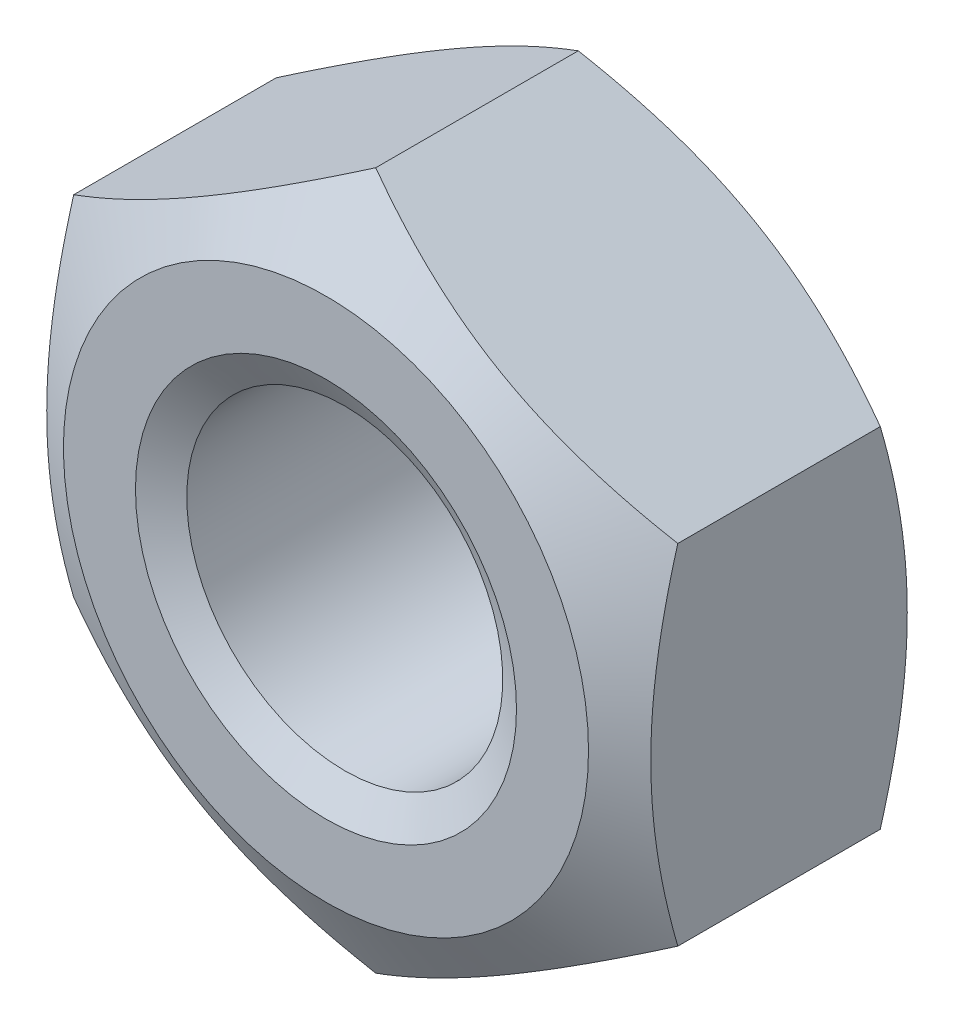
SolidWorks part; units mm, degrees
ref_plane "Front Plane" through (0, 0, 0) normal (0, 0, 1) x (1, 0, 0)
ref_plane "Top Plane" through (0, 0, 0) normal (0, 1, 0) x (1, 0, 0)
ref_plane "Right Plane" through (0, 0, 0) normal (1, 0, 0) x (0, 0, -1)
sketch "Sketch1" plane through (0, 0, 0) normal (0, 0, 1) x (1, 0, 0)
  line L0 (0, 0) -> (0, 7.5056) construction
  line L1 (0, 7.5056) -> (-6.5, 3.7528)
  line L2 (-6.5, 3.7528) -> (-6.5, -3.7528)
  line L3 (-6.5, -3.7528) -> (0, -7.5056)
  line L4 (0, -7.5056) -> (6.5, -3.7528)
  line L5 (6.5, -3.7528) -> (6.5, 3.7528)
  line L6 (6.5, 3.7528) -> (0, 7.5056)
  circle A0 centre (0, 0) radius 6.5 construction
  dimension "S DIM" = 13
extrude "Boss-Extrude1" add sketch "Sketch1" against normal blind 6.5
sketch "Sketch4" plane through (0, 0, 0) normal (1, 0, 0) x (0, 0, -1)
  line L0 (6.5, 7.5056) -> (5.4287, 7.5056)
  line L1 (6.5, 7.5056) -> (0, 7.5056) construction
  line L2 (5.4287, 7.5056) -> (6.5, 5.65)
  line L4 (6.5, 5.65) -> (6.5, 7.5056)
  line L5 (0, 0) -> (3.2979, 0) construction
  line L6 (0, 7.5056) -> (1.0713, 7.5056)
  line L7 (1.0713, 7.5056) -> (0, 5.65)
  line L9 (0, 5.65) -> (0, 7.5056)
  dimension "SAME S 1" = 11.3
  dimension "D2" = 30
  dimension "SAME S 2" = 11.3
  dimension "D4" = 30
revolve "Cut-Revolve1" cut sketch "Sketch4" angle 360 about L5
sketch "Sketch5" plane through (0, 0, 0) normal (1, 0, 0) x (0, 0, -1)
  line L0 (0, 0) -> (6.5, 0) construction
  line L1 (0, 0) -> (0, 4.1)
  line L2 (0, 5.65) -> (0, -5.65) construction
  line L3 (0, 4.1) -> (0.4041, 3.4)
  line L4 (0.4041, 3.4) -> (6.0959, 3.4)
  line L5 (6.0959, 3.4) -> (6.5, 4.1)
  line L6 (6.5, 4.1) -> (6.5, 0)
  line L8 (6.5, -5.65) -> (6.5, 5.65) construction
  line L9 (6.5, 0) -> (0, 0)
  dimension "D1" = 60
  dimension "D2" = 60
  dimension "Hole2" = 8.2
  dimension "Hole1" = 6.8
revolve "Cut-Revolve2" cut sketch "Sketch5" angle 360 about L0
cosmetic thread "Cosmetic Thread1" parameters "D2"=8
